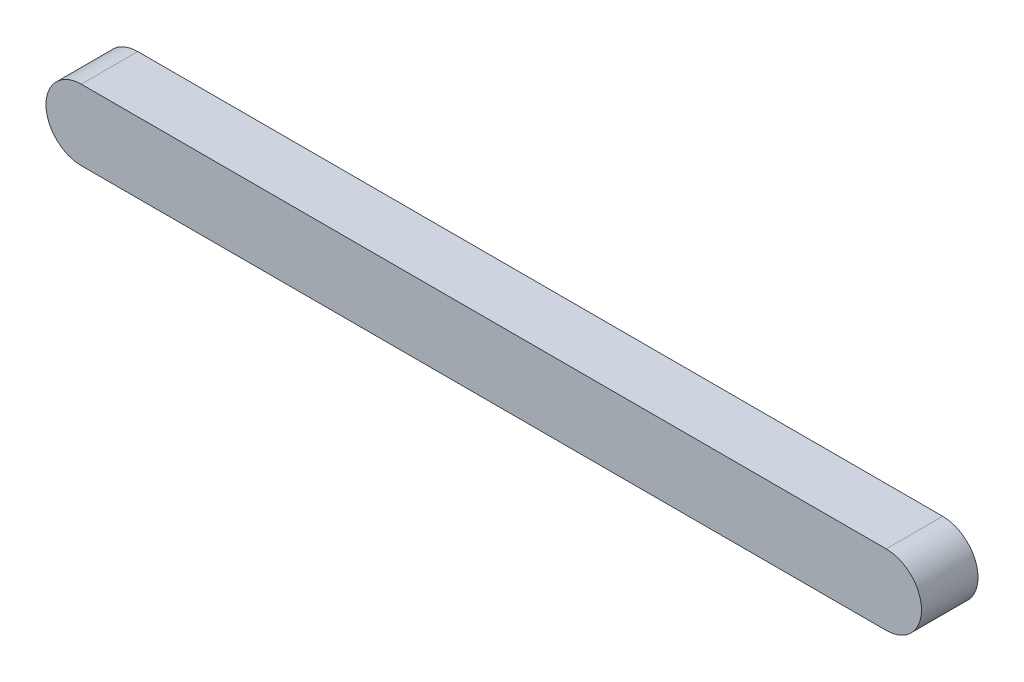
SolidWorks part; units mm, degrees
ref_plane "Спереди" through (0, 0, 0) normal (0, 0, 1) x (1, 0, 0)
ref_plane "Сверху" through (0, 0, 0) normal (0, 1, 0) x (1, 0, 0)
ref_plane "Справа" through (0, 0, 0) normal (1, 0, 0) x (0, 0, -1)
sketch "Эскиз1" plane through (0, 0, 0) normal (0, 0, 1) x (1, 0, 0)
  line L0 (0, 0) -> (114, 0) construction
  line L1 (0, 5) -> (114, 5)
  line L2 (0, -5) -> (114, -5)
  arc A0 (0, 5) -> (0, -5) centre (0, 0) ccw
  arc A1 (114, -5) -> (114, 5) centre (114, 0) ccw
  point P3 (57, 0)
  dimension "D1" = 5
  dimension "D2" = 114
extrude "Бобышка-Вытянуть3" add sketch "Эскиз1" along normal blind 8
